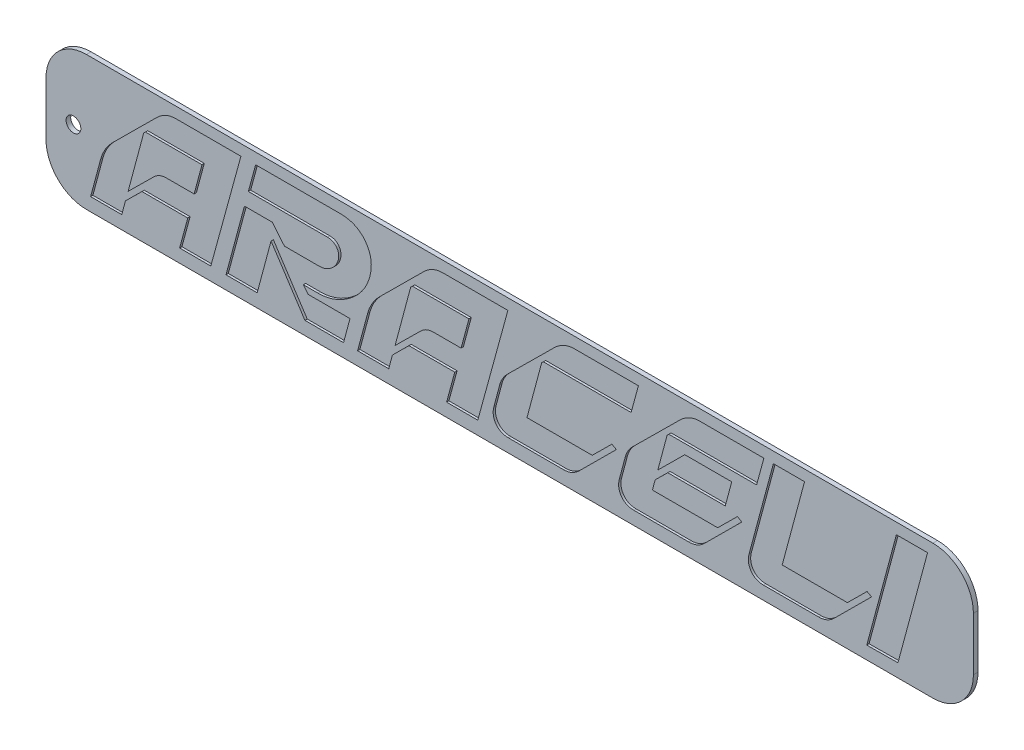
SolidWorks part; units mm, degrees
ref_plane "Front Plane" through (0, 0, 0) normal (0, 0, 1) x (1, 0, 0)
ref_plane "Top Plane" through (0, 0, 0) normal (0, 1, 0) x (1, 0, 0)
ref_plane "Right Plane" through (0, 0, 0) normal (1, 0, 0) x (0, 0, -1)
sketch "Sketch1" plane through (0, 0, 0) normal (0, 0, 1) x (1, 0, 0)
  line L0 (-38.812, 37.309) -> (-19.8627, 37.309) construction
  line L1 (-10.872, 83.6274) -> (573.1096, 83.6274)
  line L2 (-38.812, 55.6874) -> (-38.812, 18.9307)
  line L3 (-10.872, -9.0093) -> (573.1096, -9.0093)
  line L4 (601.0496, 55.6874) -> (601.0496, 18.9307)
  arc A0 (573.1096, 83.6274) -> (601.0496, 55.6874) centre (573.1096, 55.6874) cw
  arc A1 (573.1096, -9.0093) -> (601.0496, 18.9307) centre (573.1096, 18.9307) ccw
  arc A2 (-38.812, 18.9307) -> (-10.872, -9.0093) centre (-10.872, 18.9307) ccw
  arc A3 (-10.872, 83.6274) -> (-38.812, 55.6874) centre (-10.872, 55.6874) ccw
  circle A4 centre (-19.8627, 37.309) radius 5.08
  text T0 "araceli" font "Sterion" height 76.2
  dimension "D1" = 27.94
extrude "Boss-Extrude1" add sketch "Sketch1" along normal blind 3.175
sketch "Sketch2" plane through (0, 0, 3.175) normal (0, 0, 1) x (1, 0, 0)
  text T0 "araceli" font "Sterion" height 76.2
extrude "Cut-Extrude1" cut sketch "Sketch2" against normal blind 1.5875
